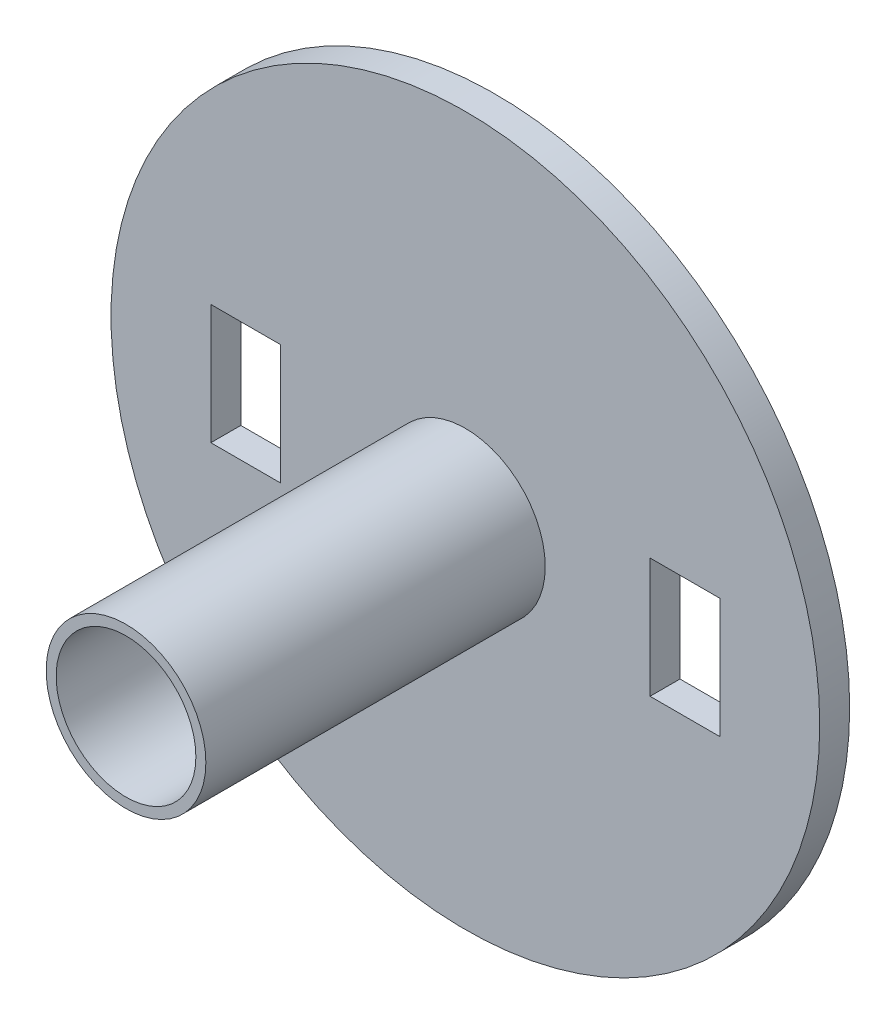
SolidWorks part; units mm, degrees
ref_plane "Front Plane" through (0, 0, 0) normal (0, 0, 1) x (1, 0, 0)
ref_plane "Top Plane" through (0, 0, 0) normal (0, 1, 0) x (1, 0, 0)
ref_plane "Right Plane" through (0, 0, 0) normal (1, 0, 0) x (0, 0, -1)
sketch "Sketch1" plane through (0, 0, 0) normal (0, 0, 1) x (1, 0, 0)
  circle A0 centre (0, 0) radius 17.75
  dimension "D1" = 35.5
extrude "Boss-Extrude1" add sketch "Sketch1" along normal blind 1.5
sketch "Sketch2" plane through (0, 0, 1.5) normal (0, 0, 1) x (1, 0, 0)
  circle A0 centre (0, 0) radius 4
  dimension "D1" = 8
extrude "Boss-Extrude2" add sketch "Sketch2" along normal blind 17
sketch "Sketch4" plane through (0, 0, 18.5) normal (0, 0, 1) x (1, 0, 0)
  line L0 (0, 0) -> (0, 11.5618) construction
  line L1 (-12.75, 3) -> (-9.25, 3)
  line L2 (-12.75, 3) -> (-12.75, -3)
  line L3 (-12.75, -3) -> (-9.25, -3)
  line L4 (-9.25, 3) -> (-9.25, -3)
  line L5 (-12.75, 3) -> (-9.25, -3) construction
  line L6 (-12.75, -3) -> (-9.25, 3) construction
  line L7 (12.75, -3) -> (9.25, -3)
  line L8 (12.75, 3) -> (12.75, -3)
  line L9 (12.75, 3) -> (9.25, 3)
  line L10 (9.25, 3) -> (9.25, -3)
  circle A0 centre (0, 0) radius 3.5
  point P3 (-11, 0)
  dimension "D1" = 7
  dimension "D2" = 3.5
  dimension "D3" = 11
  dimension "D4" = 6
extrude "Cut-Extrude1" cut sketch "Sketch4" against normal through all
